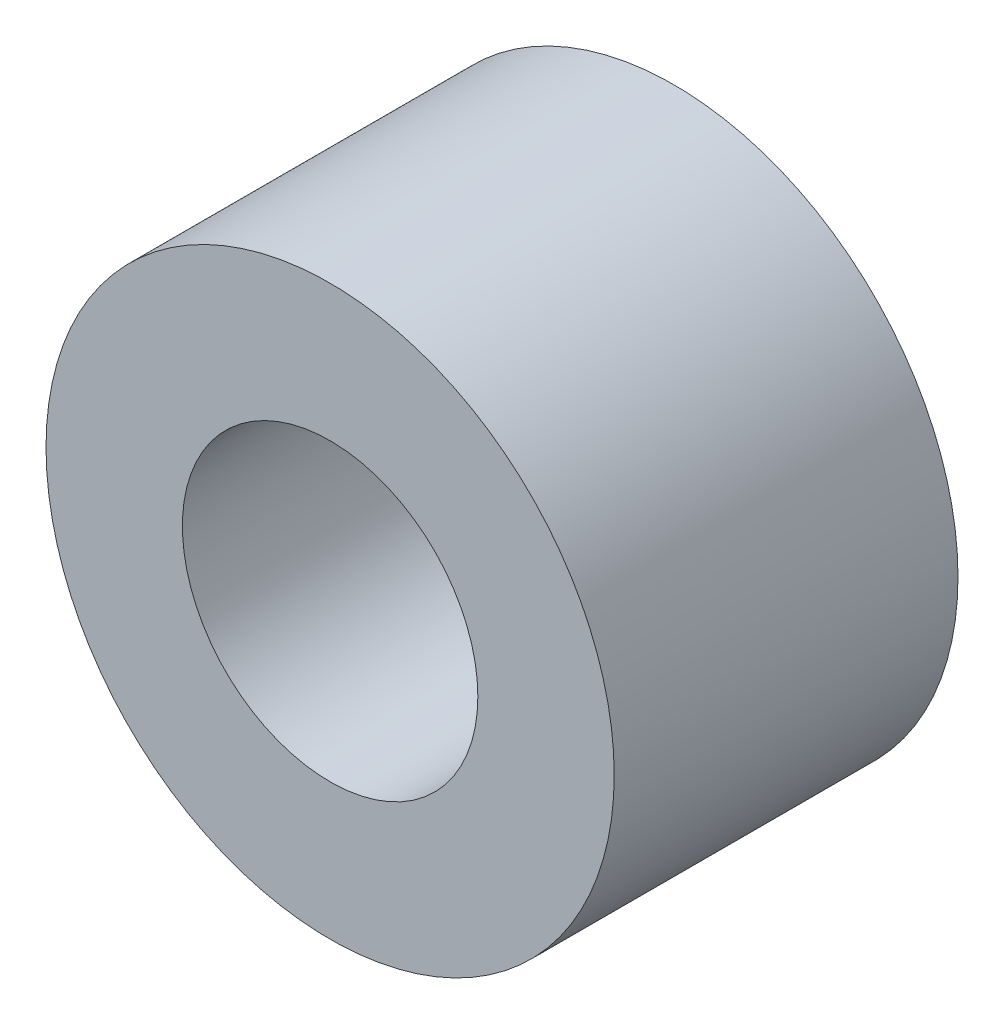
SolidWorks part; units mm, degrees
material "Delrin 2700 NC010, Low Viscosity Acetal Copolymer (SS)"
ref_plane "Front Plane" through (0, 0, 0) normal (0, 0, 1) x (1, 0, 0)
ref_plane "Top Plane" through (0, 0, 0) normal (0, 1, 0) x (1, 0, 0)
ref_plane "Right Plane" through (0, 0, 0) normal (1, 0, 0) x (0, 0, -1)
sketch "Sketch1" plane through (0, 0, 0) normal (0, 0, 1) x (1, 0, 0)
  circle A0 centre (0, 0) radius 3.302
  circle A1 centre (0, 0) radius 6.35
  dimension "D1" = 6.604
  dimension "D2" = 12.7
extrude "Boss-Extrude1" add sketch "Sketch1" along normal blind 7.6835
equation "\"D1@Boss-Extrude1\"=0.365in-.125+.0625"
